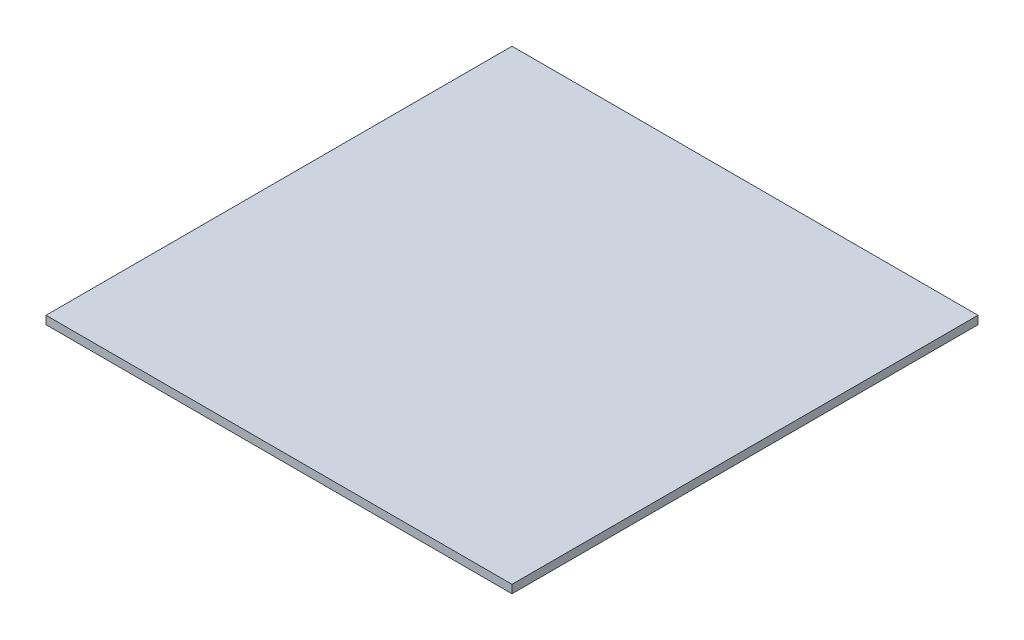
SolidWorks part; units mm, degrees
material "Acrylic (Medium-high impact)"
ref_plane "Front Plane" through (0, 0, 0) normal (0, 0, 1) x (1, 0, 0)
ref_plane "Top Plane" through (0, 0, 0) normal (0, 1, 0) x (1, 0, 0)
ref_plane "Right Plane" through (0, 0, 0) normal (1, 0, 0) x (0, 0, -1)
sketch "Sketch1" plane through (0, 0, 0) normal (0, 1, 0) x (1, 0, 0)
  line L1 (85, -85) -> (-85, -85)
  line L2 (85, -85) -> (85, 85)
  line L3 (85, 85) -> (-85, 85)
  line L4 (-85, -85) -> (-85, 85)
  line L5 (85, -85) -> (-85, 85) construction
  line L6 (85, 85) -> (-85, -85) construction
  point P0 (0, 0)
  dimension "D1" = 170
  dimension "D2" = 170
extrude "Boss-Extrude1" add sketch "Sketch1" along normal blind 3
